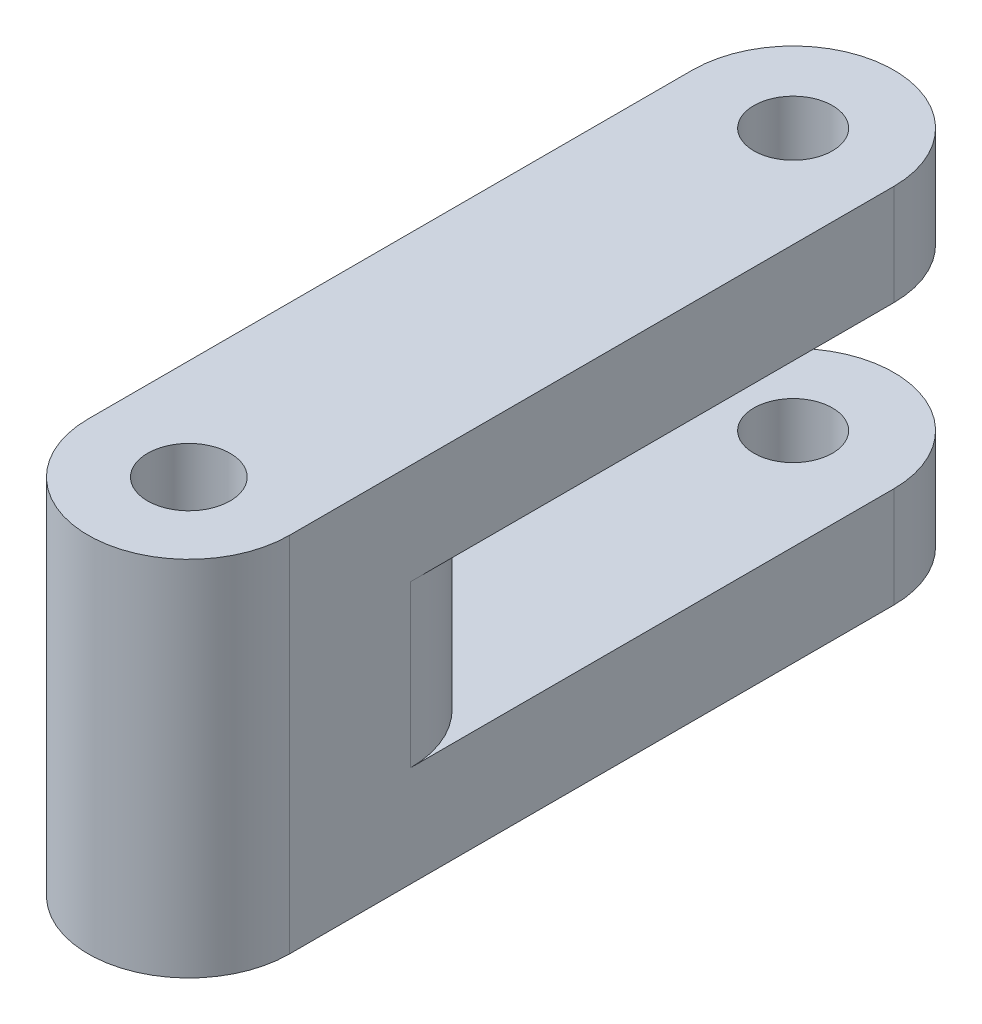
SolidWorks part; units mm, degrees
ref_plane "Plan de face" through (0, 0, 0) normal (0, 0, 1) x (1, 0, 0)
ref_plane "Plan de dessus" through (0, 0, 0) normal (0, 1, 0) x (1, 0, 0)
ref_plane "Plan de droite" through (0, 0, 0) normal (1, 0, 0) x (0, 0, -1)
sketch "Esquisse1" plane through (0, 0, 0) normal (0, 1, 0) x (1, 0, 0)
  line L0 (0, 0) -> (0, 30) construction
  line L1 (-5, 0) -> (-5, 30)
  line L2 (5, 0) -> (5, 30)
  arc A0 (-5, 0) -> (5, 0) centre (0, 0) ccw
  arc A1 (5, 30) -> (-5, 30) centre (0, 30) ccw
  circle A2 centre (0, 30) radius 1.95
  circle A3 centre (0, 0) radius 2.05
  point P3 (0, 15)
  dimension "D3" = 4.1
  dimension "D4" = 3.9
  dimension "D1" = 10
  dimension "D2" = 30
extrude "Boss.-Extru.1" add sketch "Esquisse1" along normal blind 5
sketch "Esquisse2" plane through (0, 5, 0) normal (0, 1, 0) x (1, 0, 0)
  line L0 (0, 0) -> (0, 6) construction
  line L1 (-5, 0) -> (-5, 6)
  line L2 (5, 0) -> (5, 6)
  arc A0 (-5, 0) -> (5, 0) centre (0, 0) ccw
  arc A1 (5, 6) -> (-5, 6) centre (0, 6) ccw
  arc A2 (-5, 0) -> (5, 0) centre (0, 0) ccw construction
  circle A3 centre (0, 0) radius 2.05 construction
  circle A4 centre (0, 0) radius 2.05
  point P3 (0, 3)
  dimension "D1" = 6
extrude "Boss.-Extru.2" add sketch "Esquisse2" along normal blind 8
sketch "Esquisse3" plane through (0, 5, 0) normal (0, 1, 0) x (1, 0, 0)
  line L0 (5, 0) -> (5, 6) construction
  line L1 (-5, 6) -> (-5, 0) construction
  line L2 (5, 6) -> (5, 30) construction
  line L3 (-5, 30) -> (-5, 6) construction
  line L4 (5, 0) -> (5, 6)
  line L5 (-5, 6) -> (-5, 0)
  line L6 (5, 6) -> (5, 30)
  line L7 (-5, 30) -> (-5, 6)
  arc A0 (-5, 0) -> (5, 0) centre (0, 0) ccw construction
  arc A1 (5, 6) -> (-5, 6) centre (0, 6) ccw construction
  arc A2 (5, 6) -> (-5, 6) centre (0, 6) ccw construction
  arc A3 (5, 30) -> (-5, 30) centre (0, 30) ccw construction
  arc A4 (-5, 0) -> (5, 0) centre (0, 0) ccw
  arc A5 (5, 6) -> (-5, 6) centre (0, 6) ccw
  arc A6 (5, 6) -> (-5, 6) centre (0, 6) ccw
  arc A7 (5, 30) -> (-5, 30) centre (0, 30) ccw
  circle A8 centre (0, 30) radius 1.95 construction
  circle A9 centre (0, 0) radius 2.05 construction
  circle A10 centre (0, 30) radius 1.95
  circle A11 centre (0, 0) radius 2.05
  arc M1 (-5, 6) -> (5, 6) centre (0, 6) cw
  line M2 (5, 6) -> (5, 30)
  arc M3 (5, 30) -> (-5, 30) centre (0, 30) ccw
  line M4 (-5, 30) -> (-5, 6)
  circle M5 centre (0, 30) radius 1.95
extrude "Boss.-Extru.3" add sketch "Esquisse3" along normal blind 5 from surface at 8 contours M4 M1 M2 M3 M5 | L5 A4 L4 A11 M1 starting at face at (0, 13, -3)
